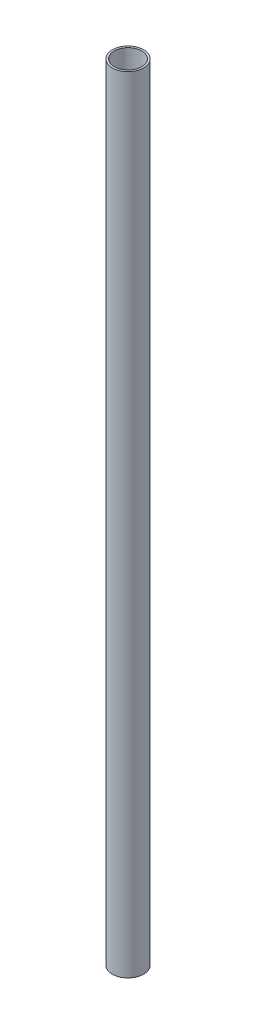
SolidWorks part; units mm, degrees
ref_plane "Front Plane" through (0, 0, 0) normal (0, 0, 1) x (1, 0, 0)
ref_plane "Top Plane" through (0, 0, 0) normal (0, 1, 0) x (1, 0, 0)
ref_plane "Right Plane" through (0, 0, 0) normal (1, 0, 0) x (0, 0, -1)
sketch "Sketch1" plane through (0, 0, 0) normal (0, 0, 1) x (1, 0, 0)
  line L1 (-4, 5) -> (4, 5)
  line L2 (-4, 5) -> (-4, 205)
  line L3 (-4, 205) -> (4, 205)
  line L4 (4, 5) -> (4, 205)
  line L5 (0, 5) -> (0, 205) construction
  dimension "D1" = 200
revolve "Revolve1" add sketch "Sketch1" angle 360 about L5
sketch "Sketch2" plane through (0, 205, 0) normal (0, 1, 0) x (1, 0, 0)
  circle A0 centre (0, 0) radius 3.5
  circle A1 centre (0, 0) radius 4 construction
  dimension "D1" = 0.5
extrude "Cut-Extrude1" cut sketch "Sketch2" against normal blind 222.5791
sketch "Sketch3" plane through (0, 0, 0) normal (1, 0, 0) x (0, 0, -1)
  circle A0 centre (0, 27.7) radius 1.5
  dimension "D1" = 3
extrude "Cut-Extrude2" cut sketch "Sketch3" against normal blind 22
